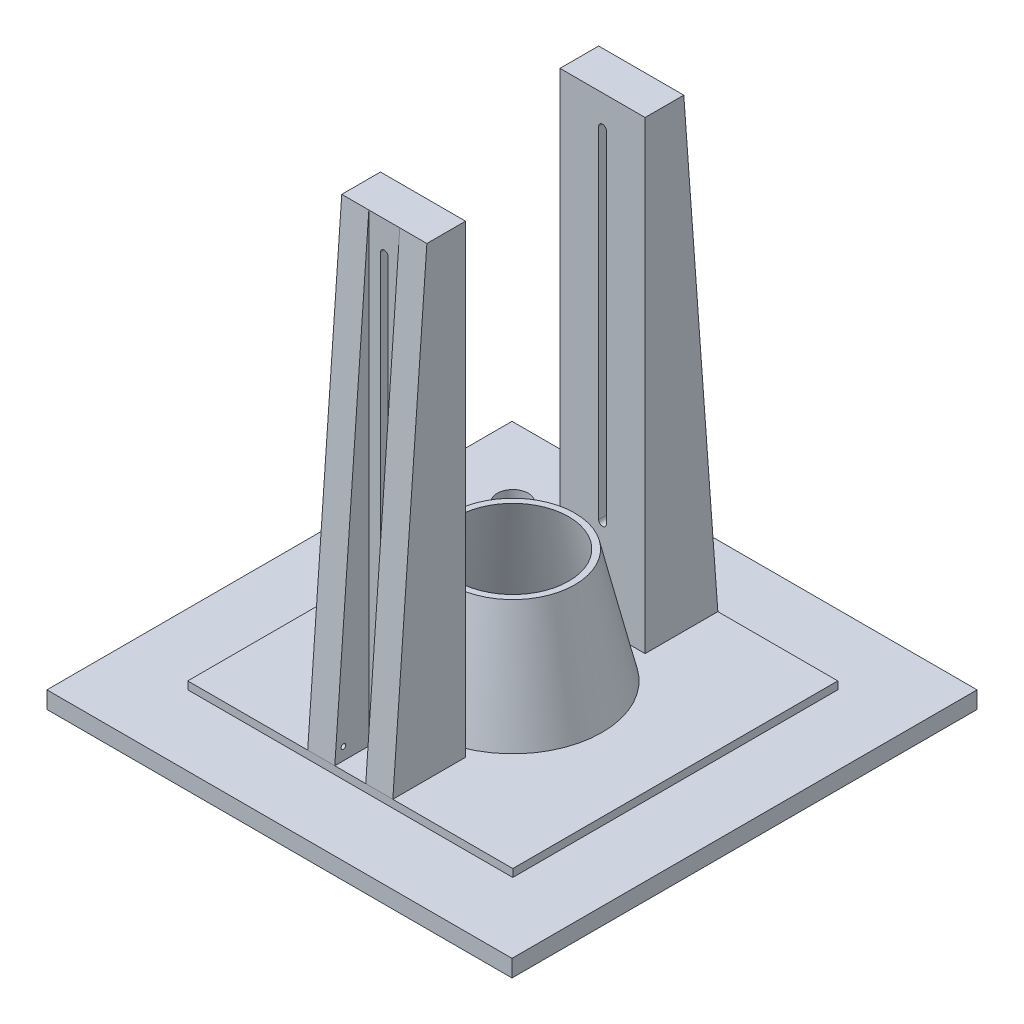
SolidWorks part; units mm, degrees
ref_plane "Front Plane" through (0, 0, 0) normal (0, 0, 1) x (1, 0, 0)
ref_plane "Top Plane" through (0, 0, 0) normal (0, 1, 0) x (1, 0, 0)
ref_plane "Right Plane" through (0, 0, 0) normal (1, 0, 0) x (0, 0, -1)
sketch "Sketch1" plane through (0, 0, 0) normal (1, 0, 0) x (0, 0, -1)
  line L2 (58, -1.1642) -> (40.125, 73.8358)
  line L11 (40.125, 73.8358) -> (36.125, 73.8358)
  line L13 (0, 0) -> (0, -72.2807) construction
  line L17 (36.125, 73.8358) -> (54, -1.1642)
  line L18 (58, -1.1642) -> (54, -1.1642)
  dimension "D1" = 36.125
  dimension "D2" = 75
  dimension "D3" = 4
  dimension "D4" = 54
revolve "Revolve1" add sketch "Sketch1" angle 360 about L13
sketch "Sketch2" plane through (0, 0, 0) normal (0, 0, 1) x (1, 0, 0)
  line L0 (-105, 0) -> (105, 0)
  line L1 (105, 0) -> (105, -5)
  line L2 (105, -5) -> (-105, -5)
  line L3 (-105, -5) -> (-105, 0)
  dimension "D1" = 210
  dimension "D2" = 105
  dimension "D3" = 5
extrude "Boss-Extrude1" add sketch "Sketch2" along normal mid plane 210
sketch "Sketch5" plane through (0, 0, 0) normal (0, 1, 0) x (1, 0, 0)
  line L0 (-121.6585, 0) -> (123.1155, 0) construction
  line L1 (-27.5013, 83) -> (-27.5013, 58)
  line L2 (-27.5013, 58) -> (27.5, 58)
  line L3 (27.5, 58) -> (27.5, 83)
  line L4 (27.5, 83) -> (-27.5013, 83)
  line L5 (105, 105) -> (-105, 105) construction
  line L6 (105, -105) -> (105, 105) construction
  line L7 (27.5, -83) -> (-27.5013, -83)
  line L8 (27.5, -58) -> (27.5, -83)
  line L9 (-27.5013, -58) -> (27.5, -58)
  line L10 (-27.5013, -83) -> (-27.5013, -58)
  dimension "D1" = 55.0013
  dimension "D2" = 25
  dimension "D3" = 22
  dimension "D4" = 77.5
extrude "Boss-Extrude2" add sketch "Sketch5" along normal blind 300
sketch "Sketch6" plane through (0, 0, 83) normal (0, 0, 1) x (1, 0, 0)
  line L0 (0, -28.5417) -> (0, 320.7888) construction
  line L1 (-2.5, 280) -> (-2.5, 60)
  line L3 (2.5, 60) -> (2.5, 280)
  line L4 (-27.5013, 300) -> (27.5, 300) construction
  line L5 (-27.5013, 0) -> (27.5, 0) construction
  arc A0 (2.5, 280) -> (-2.5, 280) centre (0, 280) ccw
  arc A1 (-2.5, 60) -> (2.5, 60) centre (0, 60) ccw
  dimension "D1" = 2.5
  dimension "D2" = 2.5
  dimension "D3" = 20
  dimension "D4" = 60
extrude "Cut-Extrude3" cut sketch "Sketch6" against normal blind 25
sketch "Sketch7" plane through (0, 0, -83) normal (0, 0, -1) x (-1, 0, 0)
  line L0 (0, 313.8785) -> (0, -35.2783) construction
  line L1 (-2.5, 280) -> (-2.5, 60)
  line L2 (2.5, 280) -> (2.5, 60)
  line L3 (-27.5, 300) -> (27.5013, 300) construction
  line L4 (-27.5, 0) -> (27.5013, 0) construction
  arc A0 (2.5, 280) -> (-2.5, 280) centre (0, 280) ccw
  arc A1 (2.5, 60) -> (-2.5, 60) centre (0, 60) cw
  dimension "D1" = 2.5
  dimension "D2" = 2.5
  dimension "D3" = 20
  dimension "D4" = 60
extrude "Cut-Extrude4" cut sketch "Sketch7" against normal blind 25
sketch "Sketch8" plane through (0, 0, 0) normal (0, 1, 0) x (1, 0, 0)
  line L1 (-137.6646, 0) -> (110.9006, 0) construction
  line L4 (10, -83) -> (10, -105)
  line L11 (27.5, -105) -> (10, -105)
  line L14 (27.5, -83) -> (27.5, -105)
  line L17 (27.5, -83) -> (10, -83)
  line L21 (105, 105) -> (-105, 105) construction
  line L22 (-27.5013, 83) -> (-10.0013, 83)
  line L23 (-27.5013, 83) -> (-27.5013, 105)
  line L24 (-27.5013, 105) -> (-10.0013, 105)
  line L25 (-10.0013, 83) -> (-10.0013, 105)
  line L26 (-10.0013, -83) -> (-10.0013, -105)
  line L27 (27.5, 83) -> (10, 83)
  line L28 (27.5, 83) -> (27.5, 105)
  line L29 (27.5, 105) -> (10, 105)
  line L30 (10, 83) -> (10, 105)
  line L31 (-27.5013, -105) -> (-10.0013, -105)
  line L32 (-27.5013, -83) -> (-27.5013, -105)
  line L33 (-27.5013, -83) -> (-10.0013, -83)
  dimension "D4" = 17.5
  dimension "D5" = 17.5
extrude "Boss-Extrude3" add sketch "Sketch8" along normal blind 300
sketch "Sketch11" plane through (27.5, 0, 0) normal (1, 0, 0) x (0, 0, -1)
  line L0 (-105, 0) -> (-83, 300)
  line L1 (-105, 300) -> (-58, 300) construction
  line L2 (-83, 300) -> (-105, 300)
  line L3 (-105, 300) -> (-105, 0)
  line L4 (-58, 300) -> (-58, 0) construction
  line L5 (0, 326.824) -> (0, -113.8871) construction
  line L6 (105, 300) -> (105, 0)
  line L7 (83, 300) -> (105, 300)
  line L8 (105, 0) -> (83, 300)
  dimension "D1" = 25
extrude "Cut-Extrude7" cut sketch "Sketch11" against normal through all
sketch "Sketch12" plane through (-27.5013, 0, 0) normal (-1, 0, 0) x (0, 0, 1)
  line L0 (105, 0) -> (83, 300) construction
  line L1 (58, 0) -> (105, 0) construction
  circle A0 centre (99.3999, 8) radius 1.5
  dimension "D1" = 3
  dimension "D2" = 5
  dimension "D3" = 8
extrude "Cut-Extrude8" cut sketch "Sketch12" against normal blind 20
sketch "Sketch13" plane through (0, -5, 0) normal (0, -1, 0) x (1, 0, 0)
  line L1 (-150.5, 150.5) -> (150, 150.5)
  line L2 (-150.5, 150.5) -> (-150.5, -150)
  line L3 (-150.5, -150) -> (150, -150)
  line L4 (150, 150.5) -> (150, -150)
  dimension "D1" = 300.5
  dimension "D2" = 300.5
  dimension "D3" = 150.5
  dimension "D4" = 150.5
extrude "Boss-Extrude4" add sketch "Sketch13" along normal blind 11
sketch "Sketch4" plane through (0, 0, 0) normal (0, 1, 0) x (1, 0, 0)
  circle A0 centre (0, 0) radius 54
  dimension "D1" = 108
extrude "Cut-Extrude2" cut sketch "Sketch4" against normal blind 20
sketch "Sketch14" plane through (0, -16, 0) normal (0, -1, 0) x (1, 0, 0)
  line L0 (150, 150.5) -> (-150.5, 150.5) construction
  line L1 (-139.5, 139.5) -> (139, 139.5)
  line L2 (-139.5, 139.5) -> (-139.5, -139)
  line L3 (-139.5, -139) -> (139, -139)
  line L4 (139, 139.5) -> (139, -139)
  line L5 (-150.5, 150.5) -> (-150.5, -150) construction
  line L6 (-150.5, -150) -> (150, -150) construction
  line L7 (150, -150) -> (150, 150.5) construction
  line L8 (-139.5, 139.5) -> (139, -139) construction
  line L9 (139, 139.5) -> (-139.5, -139) construction
  line L10 (-102, 127) -> (-52, 77)
  line L11 (-127, 102) -> (-77, 52)
  line L12 (101.5, 127) -> (51.5, 77)
  line L13 (-102, -126.5) -> (-52.6132, -77.1132)
  line L14 (-102, 127) -> (101.5, 127)
  line L15 (-102, -126.5) -> (101.5, -126.5)
  line L16 (128.2057, 103.7057) -> (128.2057, -103.2057)
  line L17 (-127, 102) -> (-127, -101.5)
  line L18 (78.2057, 53.7057) -> (78.2057, -53.2057)
  line L19 (-52.6132, -77.1132) -> (52.1132, -77.1132)
  line L20 (-77, -51.5) -> (-77, 52)
  line L21 (-52, 77) -> (51.5, 77)
  line L23 (78.2057, 53.7057) -> (128.2057, 103.7057)
  line L26 (-77, -51.5) -> (-127, -101.5)
  line L28 (52.1132, -77.1132) -> (101.5, -126.5)
  line L29 (78.2057, -53.2057) -> (128.2057, -103.2057)
  circle A0 centre (0, 0) radius 54
  point P42 (0, 0)
  dimension "D5" = 108
  dimension "D1" = 11
  dimension "D2" = 11
  dimension "D3" = 11
  dimension "D4" = 11
  dimension "D6" = 12.5
  dimension "D7" = 17.6777
  dimension "D8" = 17.6777
  dimension "D9" = 17.6777
  dimension "D10" = 17.6777
  dimension "D12" = 12.5
  dimension "D13" = 10.7943
  dimension "D14" = 12.5
  dimension "D15" = 50
  dimension "D16" = 49.3868
  dimension "D17" = 50
  dimension "D18" = 50
extrude "Boss-Extrude5" add sketch "Sketch14" along normal blind 11
sketch "Sketch16" plane through (0, -5, 0) normal (0, 1, 0) x (1, 0, 0)
  circle A0 centre (-105, 105) radius 10
  dimension "D1" = 20
extrude "Cut-Extrude9" cut sketch "Sketch16" against normal through all both and the other way through all
